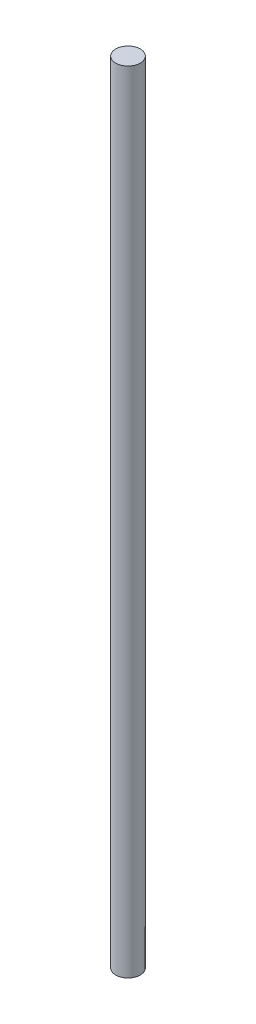
SolidWorks part; units mm, degrees
ref_plane "前视基准面" through (0, 0, 0) normal (0, 0, 1) x (1, 0, 0)
ref_plane "上视基准面" through (0, 0, 0) normal (0, 1, 0) x (1, 0, 0)
ref_plane "右视基准面" through (0, 0, 0) normal (1, 0, 0) x (0, 0, -1)
other "Configuration Table"
sketch "草图1" plane through (0, 0, 0) normal (0, 1, 0) x (1, 0, 0)
  circle A0 centre (0, 0) radius 4
  dimension "D1" = 8
extrude "凸台-拉伸1" add sketch "草图1" along normal blind 257
